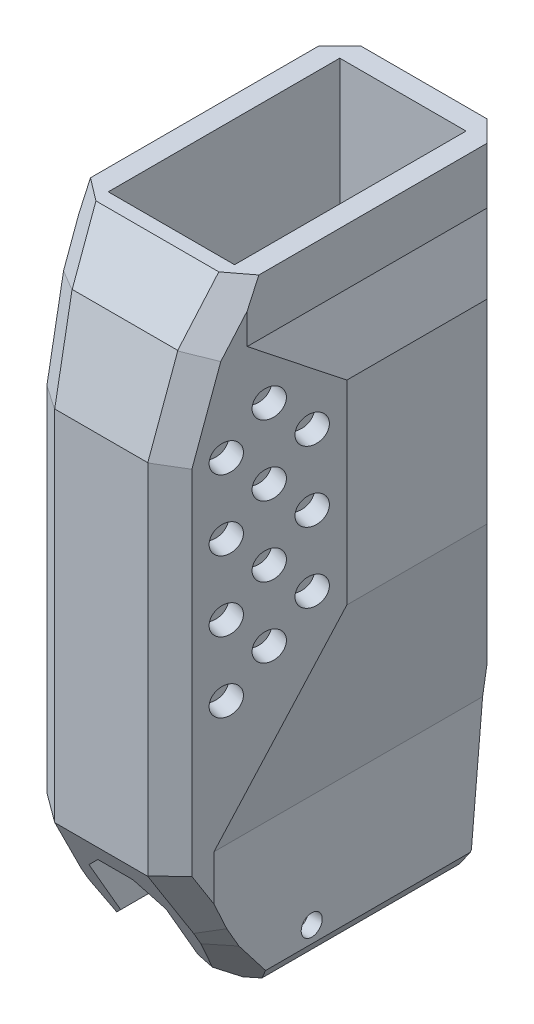
SolidWorks part; units mm, degrees
ref_plane "Plan de face" through (0, 0, 0) normal (0, 0, 1) x (1, 0, 0)
ref_plane "Plan de dessus" through (0, 0, 0) normal (0, 1, 0) x (1, 0, 0)
ref_plane "Plan de droite" through (0, 0, 0) normal (1, 0, 0) x (0, 0, -1)
sketch "Esquisse2" plane through (0, 0, 0) normal (0, 1, 0) x (1, 0, 0)
  line L0 (150, 0) -> (0, 0)
  line L1 (0, 0) -> (0, 110)
  line L2 (0, 110) -> (90, 110)
  line L3 (90, 110) -> (90, 440)
  line L4 (90, 440) -> (0, 440)
  line L5 (0, 440) -> (0, 590)
  line L6 (0, 590) -> (150, 590)
  line L7 (150, 590) -> (150, 0)
  line L8 (0, 440) -> (0, 110) construction
  dimension "D1" = 330
  dimension "D2" = 90
  dimension "D3" = 60
  dimension "D4" = 110
  dimension "D5" = 150
extrude "Boss.-Extru.1" add sketch "Esquisse2" along normal blind 890
sketch "Esquisse3" plane through (0, 0, 0) normal (0, 0, 1) x (1, 0, 0)
  line L0 (120, 810) -> (150, 727.5757)
  line L1 (0, 890) -> (150, 890) construction
  line L2 (150, 890) -> (150, 0) construction
  line L3 (150, 727.5757) -> (150, 450)
  line L4 (150, 450) -> (110, 200)
  line L5 (110, 200) -> (110, 0)
  line L6 (0, 0) -> (150, 0) construction
  line L7 (110, 0) -> (350.5953, 0)
  line L8 (350.5953, 0) -> (350.5953, 890)
  line L9 (350.5953, 890) -> (120, 890)
  line L10 (120, 890) -> (120, 810)
  line L11 (90, 890) -> (90, 0) construction
  dimension "D1" = 30
  dimension "D2" = 80
  dimension "D3" = 200
  dimension "D4" = 20
  dimension "D5" = 20
  dimension "D6" = 250
extrude "Enlèv. mat.-Extru.1" cut sketch "Esquisse3" against normal through all
sketch "Esquisse4" plane through (0, 0, 0) normal (1, 0, 0) x (0, 0, -1)
  line L0 (110, 0) -> (10, 173.2051)
  line L1 (590, 890) -> (0, 890) construction
  line L3 (10, 173.2051) -> (10, 683.812)
  line L5 (43.812, 810) -> (10, 683.812)
  line L6 (110, 0) -> (110, 173.2051) construction
  line L7 (590, 0) -> (0, 0) construction
  line L8 (110, 0) -> (440, 0)
  line L9 (440, 0) -> (520, 298.5641)
  line L10 (520, 298.5641) -> (520, 723.3975)
  line L11 (470, 890) -> (470, 810)
  line L12 (470, 890) -> (90, 890)
  line L13 (10, 173.2051) -> (110, 173.2051) construction
  line L14 (-155.9261, 947.3359) -> (734.0319, 947.3359)
  line L15 (-155.9261, 947.3359) -> (-155.9261, -125.7942)
  line L16 (-155.9261, -125.7942) -> (734.0319, -125.7942)
  line L17 (734.0319, 947.3359) -> (734.0319, -125.7942)
  line L18 (43.812, 810) -> (90, 890)
  line L19 (110, 890) -> (110, 0) construction
  line L20 (90, 890) -> (90, 810) construction
  line L21 (90, 810) -> (43.812, 810) construction
  line L22 (43.812, 810) -> (43.812, 683.812) construction
  line L23 (43.812, 683.812) -> (10, 683.812) construction
  line L24 (470, 810) -> (520, 723.3975)
  line L25 (440, 890) -> (440, 0) construction
  line L26 (470, 810) -> (470, 723.3975) construction
  line L27 (520, 723.3975) -> (470, 723.3975) construction
  line L28 (520, 298.5641) -> (440, 298.5641) construction
  line L29 (440, 298.5641) -> (440, 0) construction
  dimension "D1" = 30
  dimension "D2" = 20
  dimension "D3" = 30
  dimension "D4" = 100
  dimension "D5" = 15
  dimension "D6" = 80
  dimension "D7" = 30
  dimension "D8" = 30
  dimension "D9" = 80
  dimension "D10" = 50
  dimension "D11" = 15
extrude "Enlèv. mat.-Extru.2" cut sketch "Esquisse4" along normal through all
sketch "Esquisse5" plane through (90, 0, 0) normal (-1, 0, 0) x (0, 0, 1)
  line L0 (-400, 0) -> (-440, 80)
  line L1 (-440, 0) -> (-110, 0) construction
  line L2 (-440, 890) -> (-440, 0) construction
  line L3 (-440, 80) -> (-440, 0)
  line L4 (-440, 0) -> (-400, 0)
  line L5 (-110, 0) -> (-110, 80)
  line L6 (-110, 890) -> (-110, 0) construction
  line L7 (-110, 80) -> (-150, 0)
  line L8 (-150, 0) -> (-110, 0)
  line L9 (-110, 80) -> (-440, 80) construction
  dimension "D1" = 80
  dimension "D2" = 40
  dimension "D3" = 40
extrude "Boss.-Extru.2" add sketch "Esquisse5" along normal up to surface (90 mm away) up to face at (0, 574.5028, -62.302)
sketch "Esquisse6" plane through (0, 0, 0) normal (1, 0, 0) x (0, 0, -1)
  line L0 (200, 40) -> (130, 40) construction
  line L1 (110, 80) -> (150, 0) construction
  line L2 (200, 40) -> (200, 0) construction
  line L3 (440, 0) -> (110, 0) construction
  line L4 (110, 890) -> (110, 80) construction
  circle A0 centre (200, 40) radius 15
  dimension "D1" = 30
  dimension "D2" = 90
extrude "Enlèv. mat.-Extru.3" cut sketch "Esquisse6" along normal through all
sketch "Esquisse7" plane through (0, 0, 0) normal (0, 1, 0) x (1, 0, 0)
  line L0 (40, 520) -> (150, 410)
  line L1 (150, 520) -> (0, 520) construction
  line L2 (150, 517.5877) -> (150, 21.7264) construction
  line L3 (150, 410) -> (150, 520)
  line L4 (150, 520) -> (40, 520)
  line L5 (150, 210) -> (96.4102, 10)
  line L6 (150, 10) -> (0, 10) construction
  line L7 (96.4102, 10) -> (150, 10)
  line L8 (150, 10) -> (150, 210)
  dimension "D1" = 45
  dimension "D2" = 110
  dimension "D3" = 15
  dimension "D4" = 200
extrude "Enlèv. mat.-Extru.4" cut sketch "Esquisse7" along normal through all
chamfer "Chanfrein4" distance 30 angle 35 6 edges at (75, 167.9423, -485) (111.6581, 850, -66.906) (100.9401, 746.906, -26.906) (110, 42.6795, -85.359) (103.2051, 129.282, -35.359) (96.4102, 428.5085, -10)
sketch "Esquisse8" plane through (87.4519, 0, 23.4327) normal (0.9659, 0, 0.2588) x (0.2588, 0, -0.9659)
  line L0 (101.3818, 813.0669) -> (101.3818, 223.0716) construction
  line L1 (125.7562, 853.8459) -> (94.9792, 802.3551) construction
  line L2 (87.1191, 200) -> (241.6673, 450) construction
  line L3 (61.3818, 681.2404) -> (61.3818, 178.4955) construction
  line L4 (61.3818, 681.2404) -> (101.3818, 681.2404) construction
  line L5 (61.3818, 681.2404) -> (61.3818, 581.2404) construction
  line L6 (61.3818, 581.2404) -> (101.3818, 581.2404) construction
  line L7 (101.3818, 813.0669) -> (151.3818, 813.0669) construction
  line L8 (151.3818, 813.0669) -> (151.3818, 223.0716) construction
  line L9 (151.3818, 223.0716) -> (101.3818, 223.0716) construction
  line L10 (61.3818, 631.2404) -> (151.3818, 631.2404) construction
  line L11 (151.3818, 813.0669) -> (201.3818, 813.0669) construction
  line L12 (201.3818, 813.0669) -> (201.3818, 223.0716) construction
  line L13 (201.3818, 223.0716) -> (151.3818, 223.0716) construction
  line L14 (201.3818, 581.2404) -> (101.3818, 581.2404) construction
  circle A0 centre (101.3818, 681.2404) radius 20
  circle A1 centre (101.3818, 581.2404) radius 20
  circle A2 centre (101.3818, 481.2404) radius 20
  circle A3 centre (101.3818, 381.2404) radius 20
  circle A4 centre (151.3818, 631.2404) radius 20
  circle A5 centre (151.3818, 531.2404) radius 20
  circle A6 centre (151.3818, 431.2404) radius 20
  circle A7 centre (201.3818, 481.2404) radius 20
  circle A8 centre (201.3818, 581.2404) radius 20
  circle A9 centre (201.3818, 681.2404) radius 20
  circle A10 centre (151.3818, 731.2404) radius 20
  dimension "D1" = 40
  dimension "D4" = 100
  dimension "D5" = 50
  dimension "D6" = 40
  dimension "D8" = 100
  dimension "D11" = 40
  dimension "D12" = 100
  dimension "D13" = 40
  dimension "D14" = 100
  dimension "D2" = 40
  dimension "D9" = 50
  dimension "D3" = 4
  dimension "D7" = 3
  dimension "D10" = 2
extrude "Enlèv. mat.-Extru.5" cut sketch "Esquisse8" against normal blind 30
sketch "Esquisse9" plane through (280, 0, -280) normal (0.7071, 0, -0.7071) x (-0.7071, 0, -0.7071)
  line L0 (214.1637, 316.0211) -> (339.4113, 646.5442) construction
  line L1 (200.17, 377.865) -> (204.4675, 389.2057) construction
  line L2 (241.6741, 487.3926) -> (208.9452, 499.7948) construction
  line L3 (339.4113, 723.3975) -> (339.4113, 533.6612) construction
  line L4 (221.3474, 532.5238) -> (188.6185, 544.926) construction
  line L5 (230.1565, 245.3424) -> (339.4113, 533.6612) construction
  line L6 (183.8478, 450) -> (230.1565, 245.3424) construction
  line L7 (183.8478, 532.3364) -> (188.6185, 544.926) construction
  line L8 (200.17, 377.865) -> (333.7381, 730.3456) construction
  line L9 (339.4113, 723.3975) -> (268.7006, 810) construction
  line L10 (308.1739, 761.6553) -> (183.8478, 433.5638) construction
  line L11 (183.8478, 727.5757) -> (183.8478, 450) construction
  line L12 (183.8478, 532.3364) -> (282.6097, 792.9649) construction
  line L14 (237.1964, 376.8035) -> (204.4675, 389.2057) construction
  line L15 (225.8251, 643.1129) -> (193.0962, 655.5151) construction
  circle A0 centre (237.1964, 376.8035) radius 15 construction
  circle A1 centre (262.0009, 442.2614) radius 15
  circle A2 centre (286.8053, 507.7193) radius 15
  circle A3 centre (311.6098, 573.1772) radius 15
  circle A4 centre (216.8697, 421.9347) radius 15 construction
  circle A5 centre (221.3474, 532.5238) radius 15
  circle A6 centre (201.0207, 577.655) radius 15
  circle A7 centre (241.6741, 487.3926) radius 15
  circle A8 centre (266.4786, 552.8505) radius 15
  circle A9 centre (291.283, 618.3084) radius 15
  circle A10 centre (316.0875, 683.7664) radius 15 construction
  circle A11 centre (246.1519, 597.9817) radius 15
  circle A12 centre (270.9563, 663.4396) radius 15
  circle A13 centre (295.7608, 728.8975) radius 15 construction
  circle A14 centre (225.8251, 643.1129) radius 15
  circle A15 centre (250.6296, 708.5708) radius 15
  circle A16 centre (275.434, 774.0287) radius 15 construction
  dimension "D1" = 40
  dimension "D2" = 30
  dimension "D3" = 65
  dimension "D5" = 70
  dimension "D9" = 30
  dimension "D10" = 30
  dimension "D11" = 30
  dimension "D12" = 35
  dimension "D6" = 35
  dimension "D7" = 70
  dimension "D8" = 105
  dimension "D13" = 5
  dimension "D14" = 70
  dimension "D15" = 35
  dimension "D16" = 35
  dimension "D18" = 70
  dimension "D20" = 70
  dimension "D4" = 4
  dimension "D17" = 4
  dimension "D19" = 4
extrude "Enlèv. mat.-Extru.6" cut sketch "Esquisse9" against normal blind 20
chamfer "Chanfrein6" distance 10 angle 59 5 edges at (99.5057, 0, -432.966) (95, 0, -122.128) (110, 0, -280.0939) (44.5057, 0, -440) (40, 0, -110)
mirror "Symétrie1" about plane through (0, 890, -440) normal (1, 0, 0) of bodies 109 105
sketch "Esquisse10" plane through (0, 0, -110) normal (0, 0, -1) x (-1, 0, 0)
  line L0 (0, 173.2051) -> (0, 138.2051) construction
  line L1 (55, 138.2051) -> (-55, 138.2051)
  line L2 (55, 138.2051) -> (55, -82.5248)
  line L3 (55, -82.5248) -> (-55, -82.5248)
  line L4 (-55, 138.2051) -> (-55, -82.5248)
  line L5 (-66.1421, 173.2051) -> (66.1421, 173.2051) construction
  dimension "D1" = 110
  dimension "D2" = 35
extrude "Enlèv. mat.-Extru.7" cut sketch "Esquisse10" against normal blind 110 and the other way blind 90
sketch "Esquisse11" plane through (0, 0, -440) normal (0, 0, 1) x (1, 0, 0)
  line L0 (0, 200) -> (0, 0) construction
  line L1 (55, 200) -> (-55, 200)
  line L2 (55, 200) -> (55, -18.6213)
  line L3 (55, -18.6213) -> (-55, -18.6213)
  line L4 (-55, 200) -> (-55, -18.6213)
  line L5 (-85.9701, 0) -> (85.9701, 0) construction
  dimension "D1" = 200
  dimension "D2" = 110
extrude "Enlèv. mat.-Extru.8" cut sketch "Esquisse11" against normal blind 110 and the other way blind 100
chamfer "Chanfrein5" distance 30 angle 45 12 edges at (59.5475, 0, -110) (-59.5475, 0, -110) (-55, 138.2051, -70.1036) (-55, 0, -130) (55, 0, -130) (55, 138.2051, -70.1036) (-45.2108, 200, -487.0284) (55, 0, -415) (55, 200, -460.2335) (45.2108, 200, -487.0284) (-55, 200, -460.2335) (-55, 0, -415)
